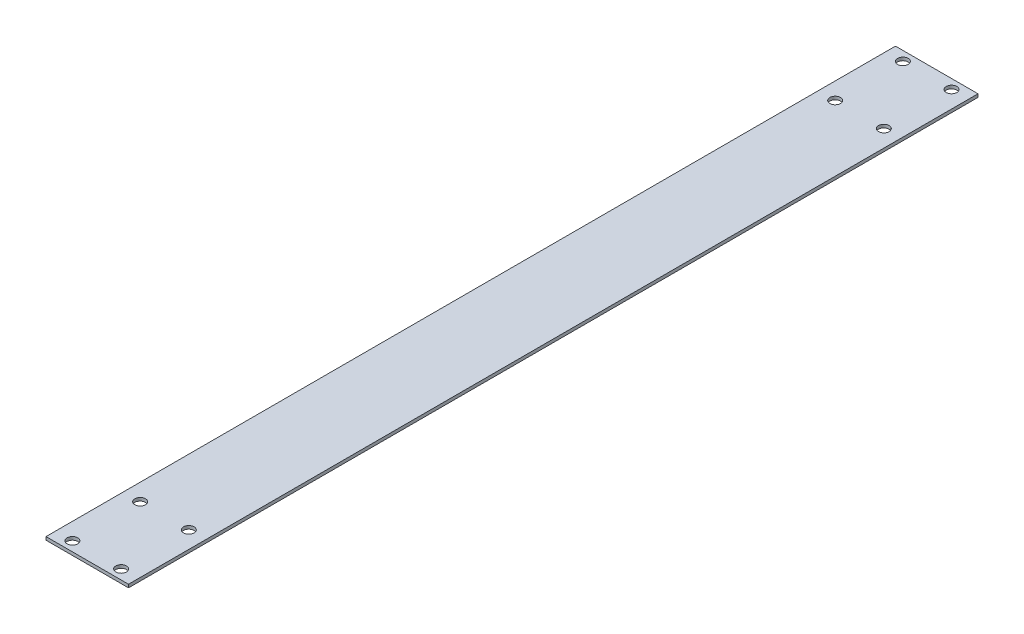
SolidWorks part; units mm, degrees
material "AISI 1020 Acier laminé à froid"
ref_plane "Plan de face" through (0, 0, 0) normal (0, 0, 1) x (1, 0, 0)
ref_plane "Plan de dessus" through (0, 0, 0) normal (0, 1, 0) x (1, 0, 0)
ref_plane "Plan de droite" through (0, 0, 0) normal (1, 0, 0) x (0, 0, -1)
sketch "Esquisse1" plane through (0, 0, 0) normal (0, 0, 1) x (1, 0, 0)
  line L1 (0, 0) -> (39, 0)
  line L2 (0, 0) -> (0, 1.5)
  line L3 (0, 1.5) -> (39, 1.5)
  line L4 (39, 0) -> (39, 1.5)
  dimension "D1" = 39
  dimension "D2" = 1.5
extrude "Boss.-Extru.1" add sketch "Esquisse1" along normal blind 401.5
sketch "Esquisse2" plane through (0, 0, 0) normal (0, 1, 0) x (1, 0, 0)
  line L0 (0, -401.5) -> (0, 0) construction
  line L1 (39, -401.5) -> (39, 0) construction
  line L2 (39, -401.5) -> (0, -401.5) construction
  line L3 (-48.8586, -200.75) -> (88.5976, -200.75) construction
  line L4 (19.5, -423.1453) -> (19.5, 17.0624) construction
  circle A0 centre (8, -397) radius 2.5
  circle A1 centre (31, -365) radius 2.5
  circle A2 centre (31, -36.5) radius 2.5
  circle A3 centre (8, -4.5) radius 2.5
  circle A4 centre (8, -36.5) radius 2.5
  circle A5 centre (31, -4.5) radius 2.5
  circle A6 centre (8, -365) radius 2.5
  circle A7 centre (31, -397) radius 2.5
  dimension "D1" = 5
  dimension "D2" = 5
  dimension "D4" = 8
  dimension "D3" = 8
  dimension "D5" = 4.5
  dimension "D6" = 36.5
  dimension "D7" = 200.75
  dimension "D8" = 19.5
extrude "Enlèv. mat.-Extru.1" cut sketch "Esquisse2" along normal through all
